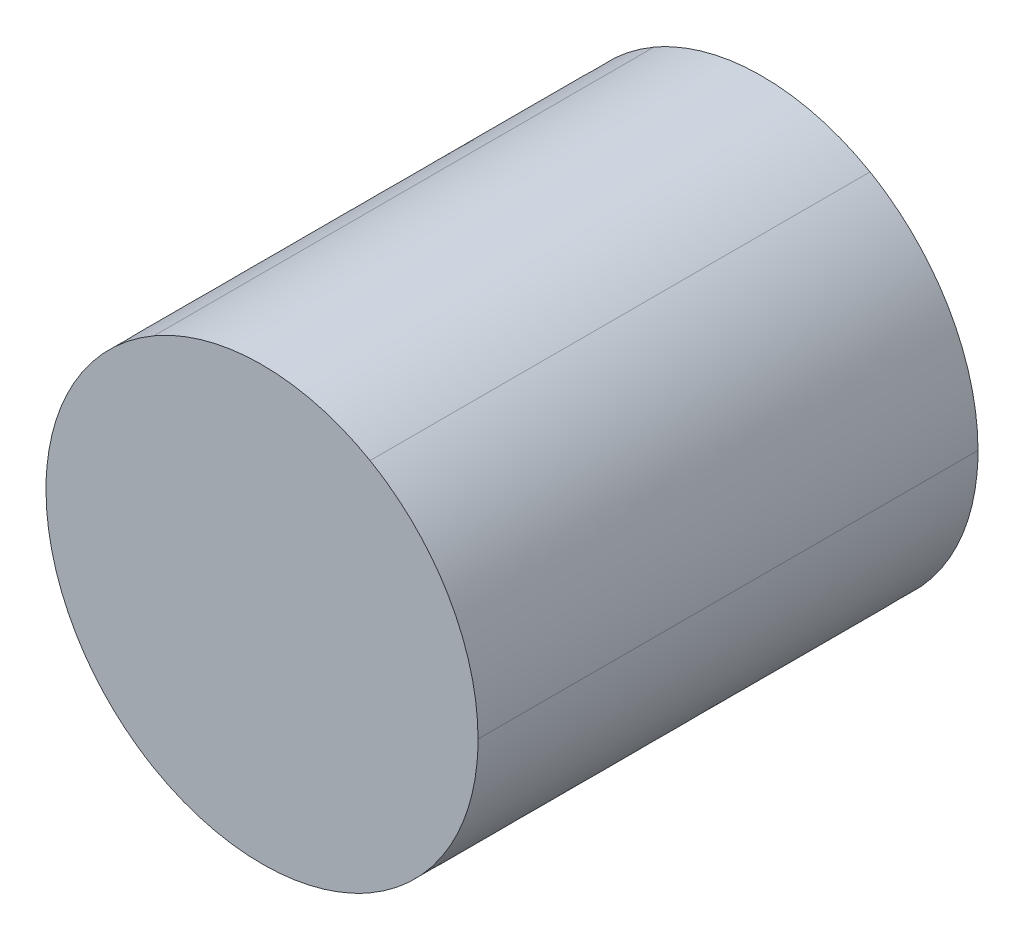
SolidWorks part; units mm, degrees
ref_plane "Front Plane" through (0, 0, 0) normal (0, 0, 1) x (1, 0, 0)
ref_plane "Top Plane" through (0, 0, 0) normal (0, 1, 0) x (1, 0, 0)
ref_plane "Right Plane" through (0, 0, 0) normal (1, 0, 0) x (0, 0, -1)
sketch "planet pin" plane through (0, 0, 0) normal (0, 0, 1) x (1, 0, 0)
  spline S0 degree 3 poles (74.1664, 167.9677) (74.1671, 166.9871) (73.6443, 166.0806) (72.7951, 165.5901) knots 0 0 0 0 1 1 1 1
  spline S1 degree 3 poles (72.7951, 165.5901) (71.9459, 165.0996) (70.8995, 165.0996) (70.0503, 165.5901) knots 0 0 0 0 1 1 1 1
  spline S2 degree 3 poles (70.0503, 165.5901) (69.2012, 166.0806) (68.6784, 166.9871) (68.679, 167.9677) knots 0 0 0 0 1 1 1 1
  spline S3 degree 3 poles (68.679, 167.9677) (68.6784, 168.9484) (69.2012, 169.8549) (70.0503, 170.3454) knots 0 0 0 0 1 1 1 1
  spline S4 degree 3 poles (70.0503, 170.3454) (70.8995, 170.8359) (71.9459, 170.8359) (72.7951, 170.3454) knots 0 0 0 0 1 1 1 1
  spline S5 degree 3 poles (72.7951, 170.3454) (73.6443, 169.8549) (74.1671, 168.9484) (74.1664, 167.9677) knots 0 0 0 0 1 1 1 1
extrude "Boss-Extrude7" add sketch "planet pin" along normal blind 6.35 separate body
